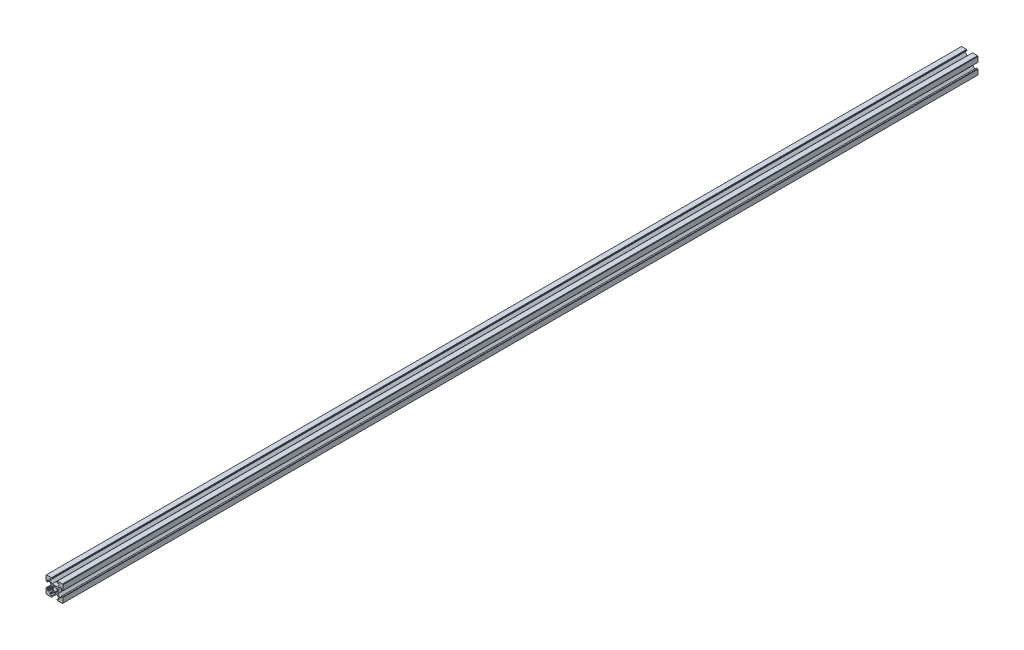
SolidWorks part; units mm, degrees
ref_plane "Front Plane" through (0, 0, 0) normal (0, 0, 1) x (1, 0, 0)
ref_plane "Top Plane" through (0, 0, 0) normal (0, 1, 0) x (1, 0, 0)
ref_plane "Right Plane" through (0, 0, 0) normal (1, 0, 0) x (0, 0, -1)
sketch "Sketch1" plane through (0, 0, 0) normal (0, 0, 1) x (1, 0, 0)
  line L0 (0, 10.7337) -> (0, 0.7337) construction
  line L1 (-9.5, 10) -> (-3.4865, 10)
  line L2 (-10, 9.5) -> (-10, 3.4865)
  line L3 (-9.5, -10) -> (-3.4865, -10)
  line L4 (10, 9.5) -> (10, 3.4865)
  line L5 (-9.75, 9.75) -> (9.75, -9.75) construction
  line L6 (-9.75, -9.75) -> (10, 10) construction
  line L7 (0, 0) -> (-10, 0) construction
  line L8 (3.1, 9.6135) -> (3.1, 8.2)
  line L9 (3.1, 8.2) -> (5, 8.2)
  line L10 (5.5, 7.7) -> (5.5, 6.5607)
  line L11 (5.5, 6.5607) -> (2.8393, 3.9)
  line L12 (2.8393, 3.9) -> (0, 3.9)
  line L13 (3.9, 2.8393) -> (3.9, 0)
  line L14 (6.5607, 5.5) -> (3.9, 2.8393)
  line L15 (9.6135, 3.1) -> (8.7, 3.1)
  line L16 (8.2, 3.6) -> (8.2, 5)
  line L17 (7.7, 5.5) -> (6.5607, 5.5)
  line L18 (3.4865, 10) -> (9.5, 10)
  line L19 (10, -3.4865) -> (10, -9.5)
  line L20 (5, 8.2) -> (5.5, 7.7)
  line L21 (8.2, 5) -> (7.7, 5.5)
  line L22 (9.5, 10) -> (10, 9.5)
  line L23 (8.7, 3.1) -> (8.2, 3.6)
  line L24 (3.9, -2.8393) -> (3.9, 0)
  line L25 (6.5607, -5.5) -> (3.9, -2.8393)
  line L26 (7.7, -5.5) -> (6.5607, -5.5)
  line L27 (8.2, -5) -> (7.7, -5.5)
  line L28 (8.2, -3.1) -> (8.2, -5)
  line L29 (9.6135, -3.1) -> (8.2, -3.1)
  line L30 (10, -3.4865) -> (10, -9.5)
  line L31 (10, -9.5) -> (9.5, -10)
  line L32 (9.5, -10) -> (3.4865, -10)
  line L33 (3.1, -9.6135) -> (3.1, -8.7)
  line L34 (3.1, -8.7) -> (3.6, -8.2)
  line L35 (3.6, -8.2) -> (5, -8.2)
  line L36 (5, -8.2) -> (5.5, -7.7)
  line L37 (5.5, -7.7) -> (5.5, -6.5607)
  line L38 (5.5, -6.5607) -> (2.8393, -3.9)
  line L39 (2.8393, -3.9) -> (0, -3.9)
  line L40 (-2.8393, -3.9) -> (0, -3.9)
  line L41 (-5.5, -6.5607) -> (-2.8393, -3.9)
  line L42 (-5.5, -7.7) -> (-5.5, -6.5607)
  line L43 (-5, -8.2) -> (-5.5, -7.7)
  line L44 (-3.1, -8.2) -> (-5, -8.2)
  line L45 (-3.1, -9.6135) -> (-3.1, -8.2)
  line L46 (-3.4865, -10) -> (-9.5, -10)
  line L47 (-9.5, -10) -> (-10, -9.5)
  line L48 (-10, -9.5) -> (-10, -3.4865)
  line L49 (-9.6135, -3.1) -> (-8.7, -3.1)
  line L50 (-8.7, -3.1) -> (-8.2, -3.6)
  line L51 (-8.2, -3.6) -> (-8.2, -5)
  line L52 (-8.2, -5) -> (-7.7, -5.5)
  line L53 (-7.7, -5.5) -> (-6.5607, -5.5)
  line L54 (-6.5607, -5.5) -> (-3.9, -2.8393)
  line L55 (-3.9, -2.8393) -> (-3.9, 0)
  line L56 (-3.9, 2.8393) -> (-3.9, 0)
  line L57 (-6.5607, 5.5) -> (-3.9, 2.8393)
  line L58 (-7.7, 5.5) -> (-6.5607, 5.5)
  line L59 (-8.2, 5) -> (-7.7, 5.5)
  line L60 (-8.2, 3.1) -> (-8.2, 5)
  line L61 (-9.6135, 3.1) -> (-8.2, 3.1)
  line L62 (-10, 3.4865) -> (-10, 9.5)
  line L63 (-10, 9.5) -> (-9.5, 10)
  line L64 (-9.5, 10) -> (-3.4865, 10)
  line L65 (-3.1, 9.6135) -> (-3.1, 8.7)
  line L66 (-3.1, 8.7) -> (-3.6, 8.2)
  line L67 (-3.6, 8.2) -> (-5, 8.2)
  line L68 (-5, 8.2) -> (-5.5, 7.7)
  line L69 (-5.5, 7.7) -> (-5.5, 6.5607)
  line L70 (-5.5, 6.5607) -> (-2.8393, 3.9)
  line L71 (-2.8393, 3.9) -> (0, 3.9)
  line L72 (3.4865, -10) -> (9.5, -10)
  line L73 (-10, -3.4865) -> (-10, -9.5)
  arc A0 (3.1, 9.6135) -> (3.4865, 10) centre (3.1, 10) ccw
  arc A1 (9.6135, 3.1) -> (10, 3.4865) centre (10, 3.1) cw
  arc A2 (9.6135, -3.1) -> (10, -3.4865) centre (10, -3.1) ccw
  arc A3 (3.1, -9.6135) -> (3.4865, -10) centre (3.1, -10) cw
  arc A4 (-3.1, -9.6135) -> (-3.4865, -10) centre (-3.1, -10) ccw
  arc A5 (-9.6135, -3.1) -> (-10, -3.4865) centre (-10, -3.1) cw
  arc A6 (-9.6135, 3.1) -> (-10, 3.4865) centre (-10, 3.1) ccw
  arc A7 (-3.1, 9.6135) -> (-3.4865, 10) centre (-3.1, 10) cw
  point P0 (0, 0)
  point P13 (5.5, 8.2)
  point P17 (3.1, 8.9068)
  point P22 (8.2, 3.1)
  point P23 (8.2, 5.5)
  point P103 (0, 0)
  dimension "D3" = 1.8
  dimension "D4" = 6.1
  dimension "D5" = 11
  dimension "D6" = 6.2
  dimension "D7" = 1.5
extrude "Boss-Extrude1" add sketch "Sketch1" along normal blind 1082 contours L65 A7 L1 L63 L2 A6 L61 L60 L59 L58 L57 L56 L55 L54 L53 L52 L51 L50 L49 A5 L48 L47 L3 A4 L45 L44 L43 L42 L41 L40 L39 L38 L37 L36 L35 L34 L33 A3 L32 L31 L19 A2 L29 L28 L27 L26 L25 L24 L13 L14 L17
hole_wizard "M6x1.0 Tapped Hole1" positions "3DSketch1" profile "Sketch2" tap size "M6x1.0" standard "ANSI Metric"
sketch3d "3DSketch1"
  line L0 (3.9, -2.8393, 1082) -> (3.9, 2.8393, 1082) construction
  line L1 (2.8393, 3.9, 1082) -> (-2.8393, 3.9, 1082) construction
  point P0 (0, 0, 0)
  point P3 (0, 0, 0)
  point P5 (0, 0, 0)
  point P7 (0.9996, -8.1302, 0)
  point P9 (0, 0, 0)
  point P11 (0, 0, 1082)
  dimension "D1" = 3.9
  dimension "D2" = 3.9
sketch "Sketch2" plane through (0, 0, 1082) normal (1, 0, 0) x (0, -1, 0)
  line L0 (0, 0) -> (0, 30)
  line L1 (0, 30) -> (2.5, 28.4978)
  line L2 (2.5, 28.4978) -> (2.5, 0.525)
  line L3 (2.5, 0.525) -> (3.025, 0)
  line L5 (3.025, 0) -> (0, 0)
  line L6 (-2.5, 0.525) -> (-3.025, 0) construction
  line L10 (0, 30) -> (-2.5, 28.4978) construction
  line L11 (0, -6.35) -> (0, 107.95) construction
  dimension "Tap Drill Dia." = 5
  dimension "Tap Drill Depth" = 30
  dimension "Near C'Sink Dia." = 6.05
  dimension "Near C'Sink Angle" = 90
  dimension "Drill Angle" = 118
cosmetic thread "Hole Thread6" parameters "D1"=12, "D2"=6
hole_wizard "M6x1.0 Tapped Hole2" positions "3DSketch2" profile "Sketch3" tap size "M6x1.0" standard "ANSI Metric"
sketch3d "3DSketch2"
  line L0 (2.8393, 3.9, 0) -> (-2.8393, 3.9, 0) construction
  line L1 (3.9, -2.8393, 0) -> (3.9, 2.8393, 0) construction
  point P3 (0, 0, 0)
  dimension "D1" = 3.9
  dimension "D2" = 3.9
sketch "Sketch3" plane through (0, 0, 0) normal (1, 0, 0) x (0, 1, 0)
  line L0 (0, 0) -> (0, 30)
  line L1 (0, 30) -> (2.5, 28.4978)
  line L2 (2.5, 28.4978) -> (2.5, 0.525)
  line L3 (2.5, 0.525) -> (3.025, 0)
  line L5 (3.025, 0) -> (0, 0)
  line L6 (-2.5, 0.525) -> (-3.025, 0) construction
  line L10 (0, 30) -> (-2.5, 28.4978) construction
  line L11 (0, -6.35) -> (0, 107.95) construction
  dimension "Tap Drill Dia." = 5
  dimension "Tap Drill Depth" = 30
  dimension "Near C'Sink Dia." = 6.05
  dimension "Near C'Sink Angle" = 90
  dimension "Drill Angle" = 118
cosmetic thread "Hole Thread7" parameters "D1"=12, "D2"=6
